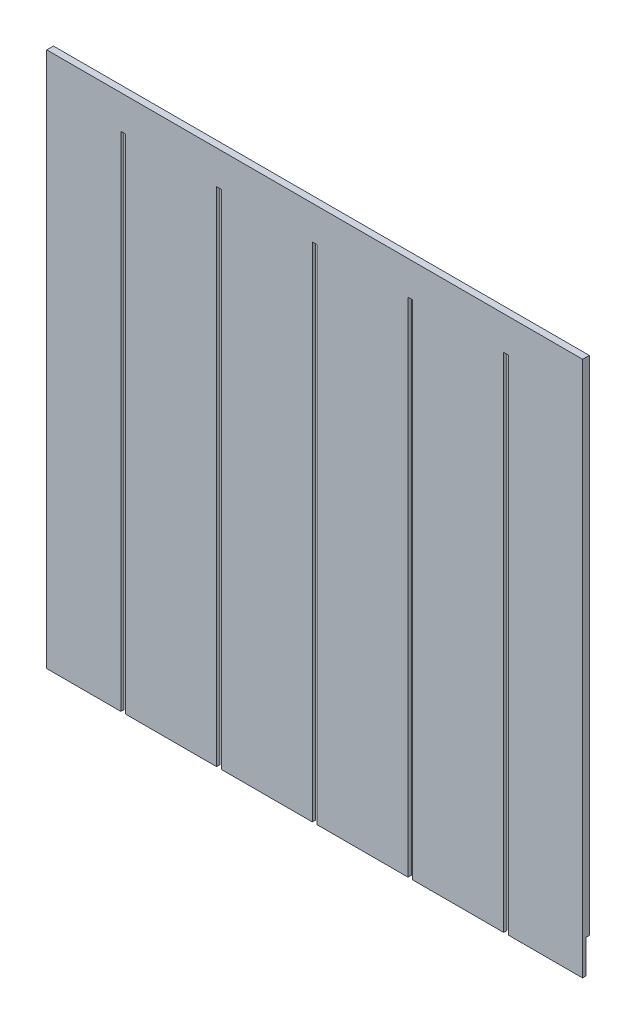
SolidWorks part; units mm, degrees
ref_plane "前视基准面" through (0, 0, 0) normal (0, 0, 1) x (1, 0, 0)
ref_plane "上视基准面" through (0, 0, 0) normal (0, 1, 0) x (1, 0, 0)
ref_plane "右视基准面" through (0, 0, 0) normal (1, 0, 0) x (0, 0, -1)
sketch "草图1" plane through (0, 0, 0) normal (0, 0, 1) x (1, 0, 0)
  line L0 (-57.86, 70) -> (-57.86, -80)
  line L1 (-62.86, -80) -> (-57.86, -80)
  line L2 (-80, -80) -> (-80, 80)
  line L3 (-80, 80) -> (80, 80)
  line L4 (80, -80) -> (80, 80)
  line L5 (-80, -80) -> (-34.28, -34.28) construction
  line L6 (-80, 80) -> (-51.46, 51.46) construction
  line L7 (-29.28, 70) -> (-29.28, -80)
  line L8 (-56.46, -80) -> (-56.46, 70)
  line L9 (-57.86, -80) -> (-62.86, -80)
  line L10 (-57.86, 70) -> (-56.46, 70)
  line L11 (-56.46, -80) -> (-29.28, -80)
  line L12 (-27.88, -80) -> (-27.88, 70)
  line L13 (-57.16, -57.5) -> (-57.16, 47.5) construction
  line L14 (80, -80) -> (57.86, -80)
  line L15 (56.46, -80) -> (29.28, -80)
  line L17 (-56.46, 70) -> (-56.46, -80)
  line L19 (-57.86, -80) -> (-62.86, -80)
  line L20 (-80, -80) -> (-62.86, -80)
  line L24 (-27.88, -80) -> (-0.7, -80)
  line L25 (-0.7, -80) -> (-27.88, -80)
  line L26 (-27.88, 70) -> (-27.88, -80)
  line L27 (-27.88, -80) -> (-0.7, -80)
  line L29 (-28.58, -57.5) -> (-28.58, 47.5) construction
  line L30 (-0.7, 70) -> (-0.7, -80)
  line L32 (0.7, -80) -> (0.7, 70)
  line L36 (0.7, -80) -> (27.88, -80)
  line L37 (27.88, -80) -> (0.7, -80)
  line L38 (0.7, 70) -> (0.7, -80)
  line L39 (0.7, -80) -> (27.88, -80)
  line L41 (0, -57.5) -> (0, 47.5) construction
  line L42 (27.88, 70) -> (27.88, -80)
  line L44 (29.28, -80) -> (29.28, 70)
  line L50 (29.28, 70) -> (29.28, -80)
  line L53 (28.58, -57.5) -> (28.58, 47.5) construction
  line L54 (56.46, 70) -> (56.46, -80)
  line L56 (57.86, -80) -> (57.86, 70)
  line L59 (-29.28, -29.28) -> (80, 80) construction
  line L62 (57.86, 70) -> (57.86, -80)
  line L65 (57.16, -57.5) -> (57.16, 47.5) construction
  line L67 (-29.28, 70) -> (-27.88, 70)
  line L73 (-0.7, 70) -> (0.7, 70)
  line L74 (27.88, 70) -> (29.28, 70)
  line L75 (56.46, 70) -> (57.86, 70)
  line L76 (-29.28, 29.28) -> (80, -80) construction
  line L77 (-34.28, -80) -> (-29.28, -80) [skipped]
  line L78 (-29.28, -80) -> (-34.28, -80) [skipped]
  line L79 (-29.28, -80) -> (-34.28, -80) [skipped]
  line L80 (-5.7, -80) -> (-0.7, -80) [skipped]
  line L81 (-0.7, -80) -> (-5.7, -80) [skipped]
  line L82 (-0.7, -80) -> (-5.7, -80) [skipped]
  line L83 (22.88, -80) -> (27.88, -80) [skipped]
  line L84 (27.88, -80) -> (22.88, -80) [skipped]
  line L85 (27.88, -80) -> (22.88, -80) [skipped]
  line L86 (51.46, -80) -> (56.46, -80) [skipped]
  line L87 (56.46, -80) -> (51.46, -80) [skipped]
  line L88 (56.46, -80) -> (51.46, -80) [skipped]
  point P0 (0, 0)
  dimension "D1" = 160
  dimension "D2" = 160
  dimension "D3" = 1.4
  dimension "D4" = 5
  dimension "D5" = 5
  dimension "D6" = 28.58
  dimension "D7" = 10
  dimension "D8" = 10
  dimension "D9" = 10
extrude "凸台-拉伸2" add sketch "草图1" along normal blind 1
sketch "草图2" plane through (0, 0, 0) normal (0, 0, -1) x (-1, 0, 0)
  line L0 (-80, -70) -> (-77.5, -70)
  line L1 (-80, -80) -> (-80, 80) construction
  line L2 (-70, -70) -> (-70, 70)
  line L3 (-80, -80) -> (-57.86, -80) construction
  line L4 (77.5, 70) -> (77.5, 72.5)
  line L5 (-70, 70) -> (72.5, 70)
  line L6 (80, -80) -> (80, 80) construction
  line L7 (80, 80) -> (-80, 80) construction
  line L8 (80, 70) -> (80, 80)
  line L9 (80, 80) -> (-80, 80)
  line L10 (-80, 80) -> (-80, -70)
  line L11 (-75, -70) -> (-75, -65.3851) construction
  line L12 (-77.5, -70) -> (-77.5, -67.5)
  line L13 (-77.5, -67.5) -> (-72.5, -67.5)
  line L14 (-72.5, -70) -> (-72.5, -67.5)
  line L15 (-72.5, -70) -> (-70, -70)
  line L16 (75, 70) -> (75, 72.5699) construction
  line L17 (72.5, 70) -> (72.5, 72.5)
  line L18 (72.5, 72.5) -> (77.5, 72.5)
  line L19 (77.5, 70) -> (80, 70)
  point P23 (-75, -67.5)
  point P30 (75, 72.5)
  dimension "D1" = 10
  dimension "D2" = 10
  dimension "D3" = 10
  dimension "D4" = 2.5
  dimension "D5" = 2.5
  dimension "D6" = 5
  dimension "D7" = 2.5
  dimension "D8" = 2.5
extrude "凸台-拉伸3" add sketch "草图2" along normal blind 1
